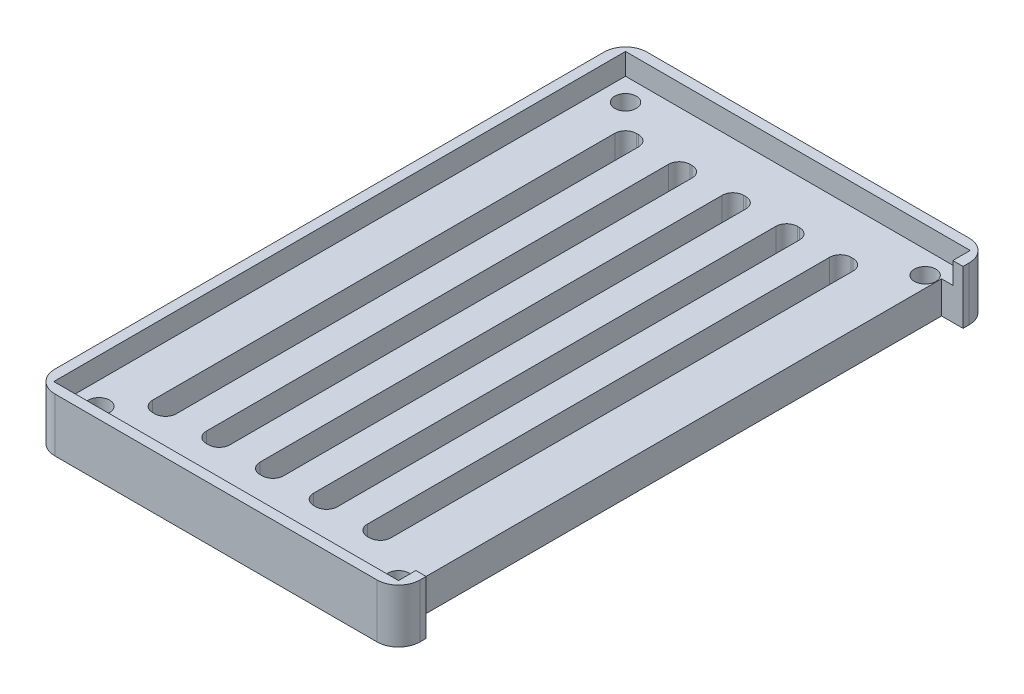
SolidWorks part; units mm, degrees
ref_plane "前视基准面" through (0, 0, 0) normal (0, 0, 1) x (1, 0, 0)
ref_plane "上视基准面" through (0, 0, 0) normal (0, 1, 0) x (1, 0, 0)
ref_plane "右视基准面" through (0, 0, 0) normal (1, 0, 0) x (0, 0, -1)
other "Configuration Table"
sketch "草图1" plane through (0, 0, 0) normal (0, 1, 0) x (1, 0, 0)
  line L1 (0, 0) -> (34, 0)
  line L2 (0, 0) -> (0, 55.14)
  line L3 (0, 55.14) -> (34, 55.14)
  line L4 (34, 0) -> (34, 55.14)
  dimension "D1" = 34
  dimension "D2" = 55.14
extrude "凸台-拉伸1" add sketch "草图1" along normal blind 5
sketch "草图2" plane through (0, 5, 0) normal (0, 1, 0) x (1, 0, 0)
  line L0 (0.95, 54.19) -> (33.05, 54.19)
  line L2 (0, 55.14) -> (0, 0)
  line L3 (0, 0) -> (34, 0)
  line L4 (34, 55.14) -> (34, 0)
  line L5 (33.05, 54.19) -> (33.05, 0.95)
  line L6 (0.95, 0.95) -> (33.05, 0.95)
  line L7 (0.95, 54.19) -> (0.95, 0.95)
  line L8 (0, 55.14) -> (34, 55.14) construction
  dimension "D1" = 0.95
extrude "切除-拉伸1" cut sketch "草图2" against normal blind 2 contours L0 L7 L6 L5
sketch "草图3" plane through (34, 0, 0) normal (1, 0, 0) x (0, 0, -1)
  line L0 (0, 5) -> (55.14, 5) construction
  line L1 (52.57, 10) -> (2.57, 10)
  line L2 (52.57, 10) -> (52.57, 0)
  line L3 (52.57, 0) -> (2.57, 0)
  line L4 (2.57, 10) -> (2.57, 0)
  line L5 (52.57, 10) -> (2.57, 0) construction
  line L6 (52.57, 0) -> (2.57, 10) construction
  line L7 (0, 0) -> (55.14, 0) construction
  point P0 (27.57, 5)
  dimension "D1" = 50
extrude "切除-拉伸2" cut sketch "草图3" against normal blind 2
fillet "圆角3" radius 2 1 edges at (0, 2.5, 0)
fillet "圆角4" radius 2 1 edges at (0, 2.5, -55.14)
fillet "圆角5" radius 2 1 edges at (34, 2.5, -55.14)
fillet "圆角6" radius 2 1 edges at (34, 2.5, 0)
sketch "草图5" plane through (0, 3, 0) normal (0, 1, 0) x (1, 0, 0)
  line L0 (17, -945.81) -> (17, 49054.19) construction
  line L1 (0.95, 54.19) -> (3.05, 54.19)
  line L2 (0.95, 54.19) -> (0.95, 52.09)
  line L3 (0.95, 52.09) -> (3.05, 52.09)
  line L4 (3.05, 54.19) -> (3.05, 52.09)
  line L6 (-999.05, 27.57) -> (49000.95, 27.57) construction
  line L7 (0.95, 54.19) -> (0.95, 0.95) construction
  line L8 (0.95, 54.19) -> (33.05, 54.19) construction
  circle A0 centre (3.05, 52.09) radius 1
  circle A1 centre (3.05, 3.05) radius 1
  circle A2 centre (30.95, 3.05) radius 1
  circle A3 centre (30.95, 52.09) radius 1
  point P13 (0.95, 27.57)
  point P16 (17, 54.19)
  dimension "D3" = 2
  dimension "D1" = 2.1
  dimension "D2" = 2.1
extrude "切除-拉伸3" cut sketch "草图5" against normal blind 5 contours A2 | A3 | A0 | A1
sketch "草图6" plane through (0, 3, 0) normal (0, 1, 0) x (1, 0, 0)
  line L0 (5.05, 49.09) -> (5.05, 6.05)
  line L1 (3.05, 52.09) -> (30.95, 52.09)
  line L2 (3.05, 52.09) -> (3.05, 3.05)
  line L3 (3.05, 3.05) -> (30.95, 3.05)
  line L4 (30.95, 52.09) -> (30.95, 3.05)
  line L5 (6.05, 5.05) -> (6.2547, 5.05)
  line L6 (28.95, 50.09) -> (28.95, 5.05)
  line L7 (6.05, 50.09) -> (6.2547, 50.09)
  line L8 (10.05, 49.09) -> (10.05, 6.05)
  line L13 (5.05, 50.09) -> (7.2547, 50.09)
  line L14 (5.05, 50.09) -> (5.05, 5.05)
  line L15 (5.05, 5.05) -> (7.2547, 5.05)
  line L16 (7.2547, 49.09) -> (7.2547, 6.05)
  line L17 (11.05, 50.09) -> (11.2547, 50.09)
  line L18 (12.2547, 49.09) -> (12.2547, 6.05)
  line L19 (11.05, 5.05) -> (11.2547, 5.05)
  line L20 (15.05, 49.09) -> (15.05, 6.05)
  line L21 (16.05, 50.09) -> (16.2547, 50.09)
  line L22 (17.2547, 49.09) -> (17.2547, 6.05)
  line L23 (16.05, 5.05) -> (16.2547, 5.05)
  line L24 (20.05, 49.09) -> (20.05, 6.05)
  line L25 (21.05, 50.09) -> (21.2547, 50.09)
  line L26 (22.2547, 49.09) -> (22.2547, 6.05)
  line L27 (21.05, 5.05) -> (21.2547, 5.05)
  line L28 (25.05, 49.09) -> (25.05, 6.05)
  line L29 (26.05, 50.09) -> (26.2547, 50.09)
  line L30 (27.2547, 49.09) -> (27.2547, 6.05)
  line L31 (26.05, 5.05) -> (26.2547, 5.05)
  line L32 (5.05, 50.09) -> (28.95, 50.09) construction
  line L33 (5.05, 5.05) -> (28.95, 5.05) construction
  line L34 (5.05, 50.09) -> (5.05, 5.05) construction
  arc A0 (6.2547, 50.09) -> (7.2547, 49.09) centre (6.2547, 49.09) cw
  arc A1 (6.2547, 5.05) -> (7.2547, 6.05) centre (6.2547, 6.05) ccw
  arc A2 (6.05, 5.05) -> (5.05, 6.05) centre (6.05, 6.05) cw
  arc A3 (5.05, 49.09) -> (6.05, 50.09) centre (6.05, 49.09) cw
  arc A4 (26.2547, 50.09) -> (27.2547, 49.09) centre (26.2547, 49.09) cw
  arc A5 (25.05, 49.09) -> (26.05, 50.09) centre (26.05, 49.09) cw
  arc A6 (26.2547, 5.05) -> (27.2547, 6.05) centre (26.2547, 6.05) ccw
  arc A7 (26.05, 5.05) -> (25.05, 6.05) centre (26.05, 6.05) cw
  arc A8 (21.2547, 5.05) -> (22.2547, 6.05) centre (21.2547, 6.05) ccw
  arc A9 (20.05, 6.05) -> (21.05, 5.05) centre (21.05, 6.05) ccw
  arc A10 (21.2547, 50.09) -> (22.2547, 49.09) centre (21.2547, 49.09) cw
  arc A11 (20.05, 49.09) -> (21.05, 50.09) centre (21.05, 49.09) cw
  arc A12 (16.2547, 50.09) -> (17.2547, 49.09) centre (16.2547, 49.09) cw
  arc A13 (15.05, 49.09) -> (16.05, 50.09) centre (16.05, 49.09) cw
  arc A14 (16.2547, 5.05) -> (17.2547, 6.05) centre (16.2547, 6.05) ccw
  arc A15 (16.05, 5.05) -> (15.05, 6.05) centre (16.05, 6.05) cw
  arc A16 (11.2547, 5.05) -> (12.2547, 6.05) centre (11.2547, 6.05) ccw
  arc A17 (10.05, 6.05) -> (11.05, 5.05) centre (11.05, 6.05) ccw
  arc A18 (11.2547, 50.09) -> (12.2547, 49.09) centre (11.2547, 49.09) cw
  arc A19 (10.05, 49.09) -> (11.05, 50.09) centre (11.05, 49.09) cw
  dimension "D3" = 1
  dimension "D4" = 1
  dimension "D1" = 2
  dimension "D2" = 5
extrude "切除-拉伸5" cut sketch "草图6" against normal blind 5 contours A3 L0 A2 L5 A1 L16 A0 L7 | A19 L8 A17 L19 A16 L18 A18 L17 | A11 L24 A9 L27 A8 L26 A10 L25 | A7 L31 A6 L30 A4 L29 A5 L28 | L20 A15 L23 A14 L22 A12 L21 A13
